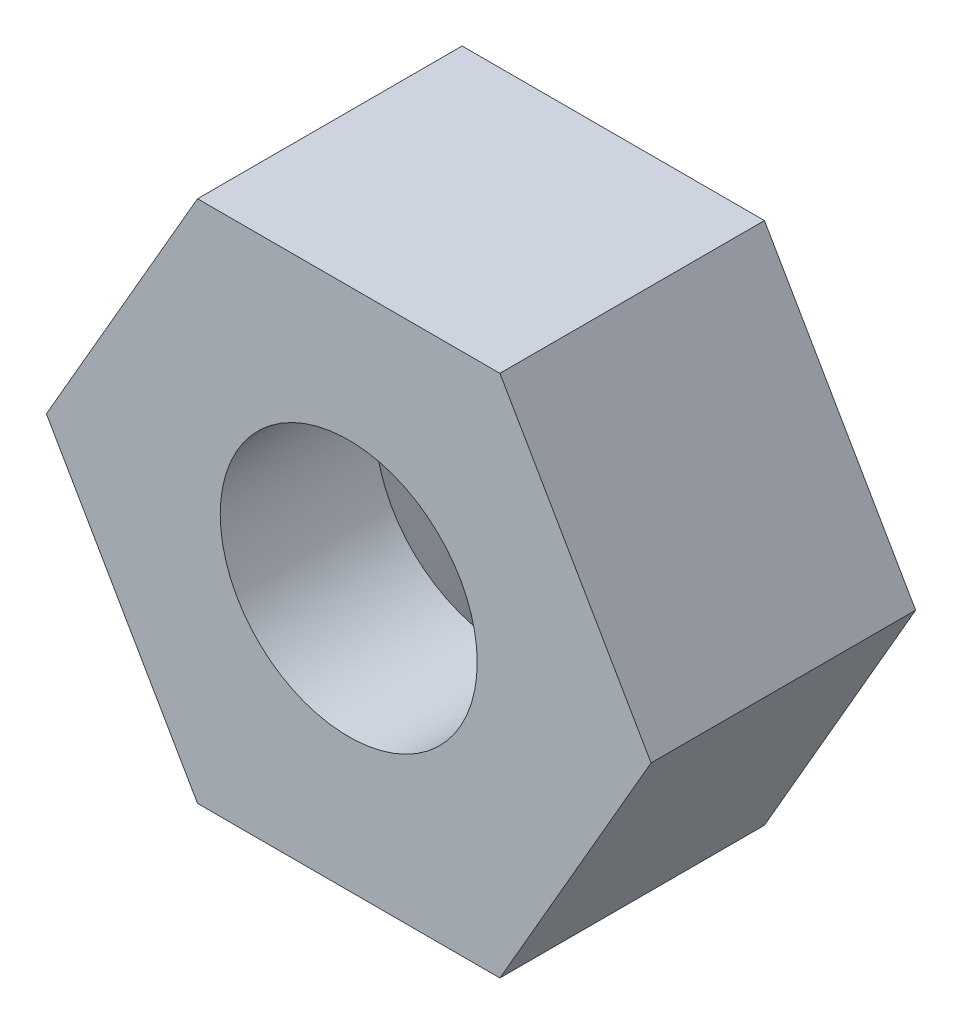
SolidWorks part; units mm, degrees
ref_plane "Front Plane" through (0, 0, 0) normal (0, 0, 1) x (1, 0, 0)
ref_plane "Top Plane" through (0, 0, 0) normal (0, 1, 0) x (1, 0, 0)
ref_plane "Right Plane" through (0, 0, 0) normal (1, 0, 0) x (0, 0, -1)
sketch "Sketch1" plane through (0, 0, 0) normal (0, 0, 1) x (1, 0, 0)
  line L1 (2, -3.4641) -> (4, 0)
  line L2 (4, 0) -> (2, 3.4641)
  line L3 (2, 3.4641) -> (-2, 3.4641)
  line L4 (-2, 3.4641) -> (-4, 0)
  line L5 (-4, 0) -> (-2, -3.4641)
  line L6 (-2, -3.4641) -> (2, -3.4641)
  circle A0 centre (0, 0) radius 3.4641 construction
  point P1 (0, 3.4641)
  dimension "D1" = 4
extrude "Boss-Extrude1" add sketch "Sketch1" along normal mid plane 3.5
hole_wizard "CSK for M3 Countersunk Flat Head Screw1" positions "Sketch4" profile "Sketch5" countersink size "M3" standard "DIN"
sketch "Sketch4" plane through (0, 0, -1.75) normal (0, 0, -1) x (-1, 0, 0)
  point P0 (0, 0)
sketch "Sketch5" plane through (0, 0, -1.75) normal (1, 0, 0) x (0, 1, 0)
  line L0 (0, 0) -> (0, 4.5215)
  line L1 (0, 4.5215) -> (1.7, 3.5)
  line L2 (1.7, 3.5) -> (1.7, 1.45)
  line L3 (1.7, 1.45) -> (3.15, 0)
  line L5 (3.15, 0) -> (0, 0)
  line L6 (-1.7, 1.45) -> (-3.15, 0) construction
  line L10 (0, 4.5215) -> (-1.7, 3.5) construction
  line L11 (0, -6.35) -> (0, 107.95) construction
  dimension "Hole Dia." = 3.4
  dimension "Hole Depth" = 3.5
  dimension "Near C'Sink Dia." = 6.3
  dimension "Near C'Sink Angle" = 90
  dimension "Drill Angle" = 118
